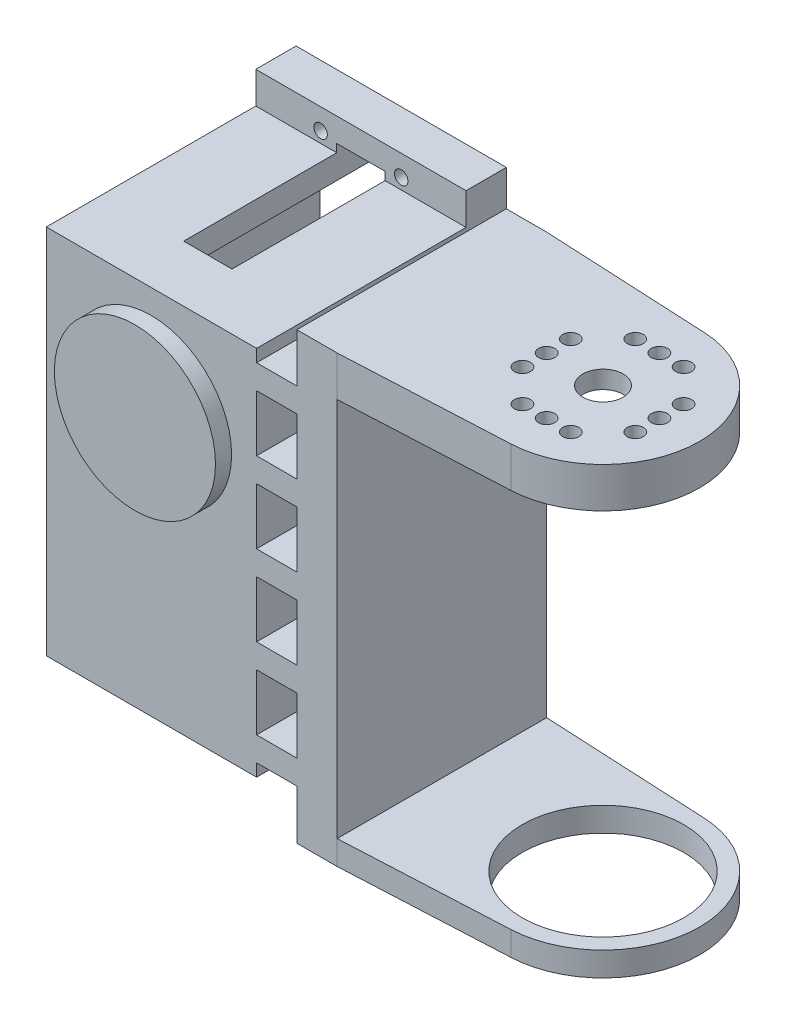
SolidWorks part; units mm, degrees
ref_plane "Front Plane" through (0, 0, 0) normal (0, 0, 1) x (1, 0, 0)
ref_plane "Top Plane" through (0, 0, 0) normal (0, 1, 0) x (1, 0, 0)
ref_plane "Right Plane" through (0, 0, 0) normal (1, 0, 0) x (0, 0, -1)
sketch "Sketch1" plane through (0, 0, 0) normal (0, 0, 1) x (1, 0, 0)
  line L0 (-13.05, 23.05) -> (13.05, 23.05)
  line L1 (-10.05, 20.05) -> (10.05, 20.05)
  line L2 (-10.05, 20.05) -> (-10.05, -20.05)
  line L3 (-10.05, -20.05) -> (10.05, -20.05)
  line L4 (10.05, 20.05) -> (10.05, -20.05)
  line L5 (-10.05, 20.05) -> (10.05, -20.05) construction
  line L6 (-10.05, -20.05) -> (10.05, 20.05) construction
  line L7 (13.05, 23.05) -> (13.05, -23.05)
  line L8 (-13.05, -23.05) -> (13.05, -23.05)
  line L9 (-13.05, 23.05) -> (-13.05, -23.05)
  point P0 (0, 0)
  dimension "D1" = 40.1
  dimension "D2" = 20.1
  dimension "D3" = 3
extrude "Boss-Extrude1" add sketch "Sketch1" along normal blind 31
sketch "Sketch2" plane through (0, 0, 31) normal (0, 0, 1) x (1, 0, 0)
  line L1 (-13.05, 23.05) -> (13.05, 23.05)
  line L2 (-13.05, 23.05) -> (-13.05, -23.05)
  line L3 (-13.05, -23.05) -> (13.05, -23.05)
  line L4 (13.05, 23.05) -> (13.05, -23.05)
  line L5 (-13.05, 23.05) -> (13.05, -23.05) construction
  line L6 (-13.05, -23.05) -> (13.05, 23.05) construction
  point P0 (0, 0)
extrude "Boss-Extrude2" add sketch "Sketch2" against normal blind 3
sketch "Sketch3" plane through (0, 0, 31) normal (0, 0, 1) x (1, 0, 0)
  line L0 (-13.05, 23.05) -> (-13.05, -23.05) construction
  line L1 (13.05, 23.05) -> (-13.05, 23.05) construction
  circle A0 centre (-0.05, 10.05) radius 10
  dimension "D3" = 20
  dimension "D1" = 13
  dimension "D2" = 13
extrude "Boss-Extrude3" add sketch "Sketch3" along normal blind 2
sketch "Sketch4" plane through (0, 0, 0) normal (0, 0, -1) x (-1, 0, 0)
  line L1 (-13.05, 27) -> (13.05, 27)
  line L2 (-13.05, 27) -> (-13.05, 23.05)
  line L3 (-13.05, 23.05) -> (13.05, 23.05)
  line L4 (13.05, 27) -> (13.05, 23.05)
  line L5 (-13.05, 27) -> (13.05, 23.05) construction
  line L6 (-13.05, 23.05) -> (13.05, 27) construction
  circle A0 centre (-5, 24.4) radius 0.8365
  circle A1 centre (5, 24.4) radius 0.8365
  point P0 (0, 25.025)
  point P6 (0, -25.025)
  dimension "D1" = 3.95
  dimension "D3" = 26.1
  dimension "D4" = 10
  dimension "D5" = 5
  dimension "D6" = 2.6
  dimension "D7" = 2.6
extrude "Boss-Extrude4" add sketch "Sketch4" against normal blind 5
mirror "Mirror1" about plane through (0, 0, 0) normal (0, 1, 0) of "Boss-Extrude4"
sketch "Sketch5" plane through (13.05, 0, 0) normal (1, 0, 0) x (0, 0, -1)
  line L0 (-31, -23.05) -> (-31, 23.05) construction
  line L1 (-31, 21.5) -> (-5, 21.5)
  line L2 (-31, 21.5) -> (-31, 18.5)
  line L3 (-31, 18.5) -> (-5, 18.5)
  line L4 (-5, 21.5) -> (-5, 18.5)
  line L5 (-31, 23.05) -> (-5, 23.05) construction
  line L6 (0, -27) -> (0, 27) construction
  line L7 (-31, 11.5) -> (-31, 8.5)
  line L8 (-31, 11.5) -> (-5, 11.5)
  line L9 (-5, 11.5) -> (-5, 8.5)
  line L10 (-31, 8.5) -> (-5, 8.5)
  line L11 (-31, 1.5) -> (-31, -1.5)
  line L12 (-31, 1.5) -> (-5, 1.5)
  line L13 (-5, 1.5) -> (-5, -1.5)
  line L14 (-31, -1.5) -> (-5, -1.5)
  line L15 (-31, -8.5) -> (-31, -11.5)
  line L16 (-31, -8.5) -> (-5, -8.5)
  line L17 (-5, -8.5) -> (-5, -11.5)
  line L18 (-31, -11.5) -> (-5, -11.5)
  line L19 (-31, -18.5) -> (-31, -21.5)
  line L20 (-31, -18.5) -> (-5, -18.5)
  line L21 (-5, -18.5) -> (-5, -21.5)
  line L22 (-31, -21.5) -> (-5, -21.5)
  line L23 (-31, -23.05) -> (-5, -23.05) construction
  dimension "D1" = 1.55
  dimension "D2" = 3
  dimension "D3" = 5
  dimension "D4" = 5
  dimension "D5" = 26
  dimension "D6" = 1.55
extrude "Boss-Extrude5" add sketch "Sketch5" along normal blind 5
sketch "Sketch7" plane through (18.05, 0, 0) normal (1, 0, 0) x (0, 0, -1)
  line L0 (-31, 20.05) -> (-31, 0.05) construction
  line L1 (-31, 27.55) -> (-5, 27.55)
  line L2 (-31, 27.55) -> (-31, -27.65)
  line L3 (-31, -27.65) -> (-5, -27.65)
  line L4 (-5, 27.55) -> (-5, -27.65)
  line L6 (-31, -23.05) -> (-5, -23.05) construction
  dimension "D1" = 26
  dimension "D2" = 0
  dimension "D3" = 55.2
  dimension "D4" = 4.6
extrude "Boss-Extrude6" add sketch "Sketch7" along normal blind 5
sketch "Sketch8" plane through (0, 27.55, 0) normal (0, 1, 0) x (1, 0, 0)
  line L0 (18.05, -31) -> (13.05, -31) construction
  line L1 (23.05, -5) -> (23.05, -31) construction
  line L2 (23.05, -5) -> (43.6405, -6.0145)
  line L3 (23.05, -31) -> (43.6405, -29.9855)
  circle A0 centre (43.05, -18) radius 12
  line M5 (23.05, -31) -> (23.05, -5)
  dimension "D1" = 24
  dimension "D2" = 13
  dimension "D3" = 20
extrude "Boss-Extrude7" add sketch "Sketch8" against normal blind 55.2 contours A0 L2 L3 M5 | A0 L2
sketch "Sketch9" plane through (0, 27.55, 0) normal (0, 1, 0) x (1, 0, 0)
  line L0 (18.05, -5) -> (13.05, -5) construction
  circle A0 centre (43.05, -18) radius 2.5
  arc A1 (43.6405, -29.9855) -> (43.6405, -6.0145) centre (43.05, -18) ccw construction
  circle A2 centre (50.05, -15) radius 1
  circle A3 centre (50.05, -18) radius 1
  circle A4 centre (50.05, -21) radius 1
  circle A5 centre (46.05, -25) radius 1
  circle A6 centre (43.05, -25) radius 1
  circle A7 centre (40.05, -25) radius 1
  circle A8 centre (36.05, -21) radius 1
  circle A9 centre (36.05, -18) radius 1
  circle A10 centre (36.05, -15) radius 1
  circle A11 centre (40.05, -11) radius 1
  circle A12 centre (43.05, -11) radius 1
  circle A13 centre (46.05, -11) radius 1
  point P34 (43.05, -18)
  dimension "D1" = 5
  dimension "D4" = 2
  dimension "D2" = 0
  dimension "D3" = 13
  dimension "D5" = 3
  dimension "D6" = 3
  dimension "D7" = 0
  dimension "D9" = 7
  dimension "D10" = 0
  dimension "D8" = 4
extrude "Cut-Extrude1" cut sketch "Sketch9" against normal blind 13.2
sketch "Sketch10" plane through (0, -27.65, 0) normal (0, -1, 0) x (1, 0, 0)
  line L0 (18.05, 5) -> (13.05, 5) construction
  circle A0 centre (43.05, 18) radius 10.025
  arc A1 (43.6405, 6.0145) -> (43.6405, 29.9855) centre (43.05, 18) ccw construction
  dimension "D1" = 20.05
  dimension "D2" = 0
  dimension "D3" = 13
extrude "Cut-Extrude2" cut sketch "Sketch10" against normal blind 13.2
sketch "Sketch11" plane through (0, 0, 5) normal (0, 0, -1) x (-1, 0, 0)
  line L0 (-23.05, -27.65) -> (-23.05, 27.55) construction
  line L1 (-23.05, 22.55) -> (-60.3854, 22.55)
  line L2 (-23.05, 22.55) -> (-23.05, -24.65)
  line L3 (-23.05, -24.65) -> (-60.3854, -24.65)
  line L4 (-60.3854, 22.55) -> (-60.3854, -24.65)
  line L5 (-23.05, 27.55) -> (-43.6405, 27.55) construction
  line L6 (-23.05, -27.65) -> (-43.6405, -27.65) construction
  dimension "D1" = 5
  dimension "D2" = 3
extrude "Cut-Extrude3" cut sketch "Sketch11" against normal blind 43.2
sketch "Sketch12" plane through (0, 22.55, 0) normal (0, -1, 0) x (1, 0, 0)
  circle A0 centre (43.05, 18) radius 10.025
extrude "Cut-Extrude4" cut sketch "Sketch12" against normal blind 2.8
sketch "Sketch13" plane through (0, 0, 0) normal (0, 0, -1) x (-1, 0, 0)
  line L0 (-10.05, 20.05) -> (10.05, 20.05) construction
  line L1 (-3, 24.05) -> (3, 24.05)
  line L2 (-3, 24.05) -> (-3, 20.05)
  line L3 (-3, 20.05) -> (3, 20.05)
  line L4 (3, 24.05) -> (3, 20.05)
  line L5 (-3, 24.05) -> (3, 20.05) construction
  line L6 (-3, 20.05) -> (3, 24.05) construction
  point P0 (0, 22.05)
  dimension "D1" = 4
  dimension "D2" = 6
  dimension "D3" = 0
extrude "Cut-Extrude5" cut sketch "Sketch13" against normal blind 24
